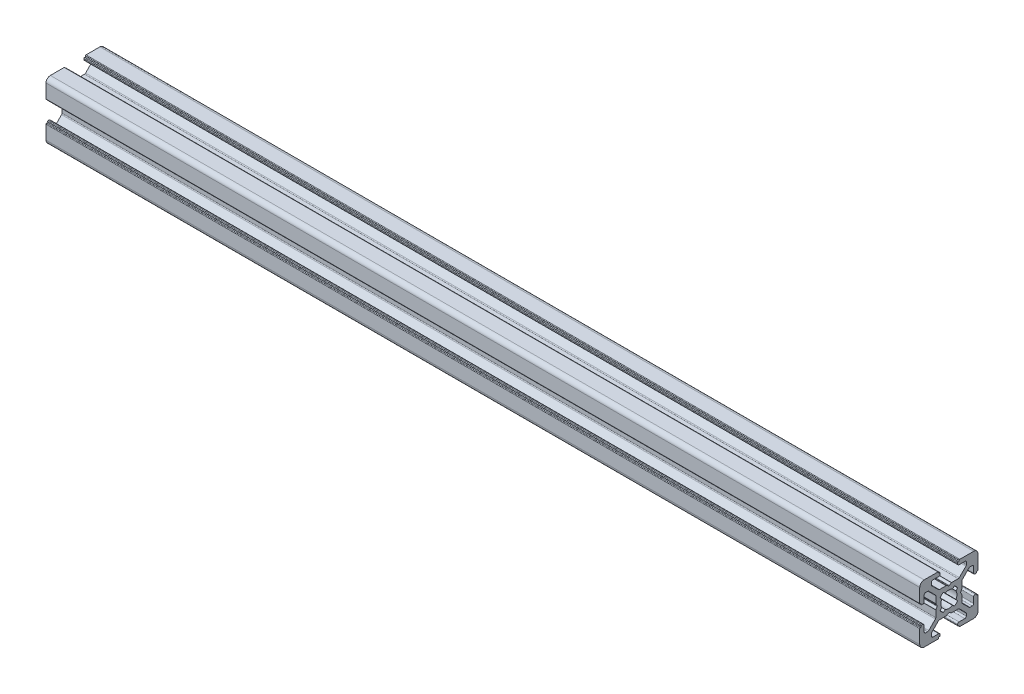
SolidWorks part; units mm, degrees
ref_plane "Front Plane" through (0, 0, 0) normal (0, 0, 1) x (1, 0, 0)
ref_plane "Top Plane" through (0, 0, 0) normal (0, 1, 0) x (1, 0, 0)
ref_plane "Right Plane" through (0, 0, 0) normal (1, 0, 0) x (0, 0, -1)
sketch "Sketch1" plane through (0, 0, 0) normal (0, 0, 1) x (1, 0, 0)
  line L0 (0, 0) -> (300, 0)
  dimension "D1" = 300
other "Metric 2020(1)"
ref_plane "Plane1" through (0, 0, 0) normal (1, 0, 0) x (0, 1, 0)
sketch "Sketch11" plane through (0, 0, 0) normal (1, 0, 0) x (0, 1, 0)
  line L0 (0, 10) -> (0, -10) construction
  line L1 (-10, 0) -> (10, 0) construction
  line L2 (-3.5, 8.5) -> (-5.5, 8.5)
  line L3 (-3.55, 9.7) -> (-3.55, 9.8)
  line L4 (-6, 7.2678) -> (-6, 8)
  line L5 (-7.2678, 6) -> (-8, 6)
  line L6 (-3.75, 10) -> (-8.5, 10)
  line L7 (-9.7, 3.55) -> (-9.8, 3.55)
  line L8 (-9.5, 3.2) -> (-9.5, 3.35)
  line L9 (-9, 3) -> (-9.3, 3)
  line L10 (-4.4732, 0.8536) -> (-4.0381, 0.1)
  line L11 (-4.5, 3.2322) -> (-4.5, 0.9536)
  line L12 (-8.5, 3.5) -> (-8.5, 5.5)
  line L13 (-10, 3.75) -> (-10, 8.5)
  line L14 (-3.5858, 4.6464) -> (-5.8536, 6.9142)
  line L15 (-4.6464, 3.5858) -> (-6.9142, 5.8536)
  line L16 (-3.2, 9.5) -> (-3.35, 9.5)
  line L17 (-3, 9) -> (-3, 9.3)
  line L18 (-0.8536, 4.4732) -> (-0.1, 4.0381)
  line L19 (-3.2322, 4.5) -> (-0.9536, 4.5)
  line L20 (-1.2582, 2.4453) -> (-1.9139, 2.9896)
  line L21 (-2.4453, 1.2582) -> (-2.9922, 1.9099)
  line L22 (3.5, -8.5) -> (5.5, -8.5)
  line L23 (3.55, -9.7) -> (3.55, -9.8)
  line L24 (6, -7.2678) -> (6, -8)
  line L25 (7.2678, -6) -> (8, -6)
  line L26 (3.75, -10) -> (8.5, -10)
  line L27 (9.7, -3.55) -> (9.8, -3.55)
  line L28 (9.5, -3.2) -> (9.5, -3.35)
  line L29 (9, -3) -> (9.3, -3)
  line L30 (4.4732, -0.8536) -> (4.0381, -0.1)
  line L31 (4.5, -3.2322) -> (4.5, -0.9536)
  line L32 (8.5, -3.5) -> (8.5, -5.5)
  line L33 (10, -3.75) -> (10, -8.5)
  line L34 (3.5858, -4.6464) -> (5.8536, -6.9142)
  line L35 (4.6464, -3.5858) -> (6.9142, -5.8536)
  line L36 (3.2, -9.5) -> (3.35, -9.5)
  line L37 (3, -9) -> (3, -9.3)
  line L38 (0.8536, -4.4732) -> (0.1, -4.0381)
  line L39 (3.2322, -4.5) -> (0.9536, -4.5)
  line L40 (1.2582, -2.4453) -> (1.9139, -2.9896)
  line L41 (2.4453, -1.2582) -> (2.9922, -1.9099)
  line L42 (-2.4453, -1.2582) -> (-2.9922, -1.9099)
  line L43 (-1.2582, -2.4453) -> (-1.9139, -2.9896)
  line L44 (-3.2322, -4.5) -> (-0.9536, -4.5)
  line L45 (-0.8536, -4.4732) -> (-0.1, -4.0381)
  line L46 (-3, -9) -> (-3, -9.3)
  line L47 (-3.2, -9.5) -> (-3.35, -9.5)
  line L48 (-4.6464, -3.5858) -> (-6.9142, -5.8536)
  line L49 (-3.5858, -4.6464) -> (-5.8536, -6.9142)
  line L50 (-10, -3.75) -> (-10, -8.5)
  line L51 (-8.5, -3.5) -> (-8.5, -5.5)
  line L52 (-4.5, -3.2322) -> (-4.5, -0.9536)
  line L53 (-4.4732, -0.8536) -> (-4.0381, -0.1)
  line L54 (-9, -3) -> (-9.3, -3)
  line L55 (-9.5, -3.2) -> (-9.5, -3.35)
  line L56 (-9.7, -3.55) -> (-9.8, -3.55)
  line L57 (2.4453, 1.2582) -> (2.9922, 1.9099)
  line L58 (1.2582, 2.4453) -> (1.9139, 2.9896)
  line L59 (3.2322, 4.5) -> (0.9536, 4.5)
  line L60 (0.8536, 4.4732) -> (0.1, 4.0381)
  line L61 (-3.75, -10) -> (-8.5, -10)
  line L62 (-7.2678, -6) -> (-8, -6)
  line L63 (-6, -7.2678) -> (-6, -8)
  line L64 (3, 9) -> (3, 9.3)
  line L65 (3.2, 9.5) -> (3.35, 9.5)
  line L66 (4.6464, 3.5858) -> (6.9142, 5.8536)
  line L67 (3.5858, 4.6464) -> (5.8536, 6.9142)
  line L68 (10, 3.75) -> (10, 8.5)
  line L69 (8.5, 3.5) -> (8.5, 5.5)
  line L70 (4.5, 3.2322) -> (4.5, 0.9536)
  line L71 (4.4732, 0.8536) -> (4.0381, 0.1)
  line L72 (9, 3) -> (9.3, 3)
  line L73 (9.5, 3.2) -> (9.5, 3.35)
  line L74 (9.7, 3.55) -> (9.8, 3.55)
  line L75 (3.75, 10) -> (8.5, 10)
  line L76 (7.2678, 6) -> (8, 6)
  line L77 (6, 7.2678) -> (6, 8)
  line L78 (3.55, 9.7) -> (3.55, 9.8)
  line L79 (3.5, 8.5) -> (5.5, 8.5)
  line L80 (-3.55, -9.7) -> (-3.55, -9.8)
  line L81 (-3.5, -8.5) -> (-5.5, -8.5)
  line L83 (10, -10) -> (-10, -10) construction
  line L84 (10, -10) -> (10, 10) construction
  line L85 (10, 10) -> (-10, 10) construction
  line L86 (-10, -10) -> (-10, 10) construction
  line L87 (10, -10) -> (-10, 10) construction
  line L88 (10, 10) -> (-10, -10) construction
  arc A0 (-10, 8.5) -> (-8.5, 10) centre (-8.5, 8.5) cw
  arc A1 (-8.5, 5.5) -> (-8, 6) centre (-8, 5.5) cw
  arc A2 (-7.2678, 6) -> (-6.9142, 5.8536) centre (-7.2678, 5.5) cw
  arc A3 (-5.8536, 6.9142) -> (-6, 7.2678) centre (-5.5, 7.2678) cw
  arc A4 (-6, 8) -> (-5.5, 8.5) centre (-5.5, 8) cw
  arc A5 (-9.7, 3.55) -> (-9.5, 3.35) centre (-9.7, 3.35) cw
  arc A6 (-9.8, 3.55) -> (-10, 3.75) centre (-9.8, 3.75) cw
  arc A7 (-9.3, 3) -> (-9.5, 3.2) centre (-9.3, 3.2) cw
  arc A8 (-8.5, 3.5) -> (-9, 3) centre (-9, 3.5) cw
  arc A9 (-4.6464, 3.5858) -> (-4.5, 3.2322) centre (-5, 3.2322) cw
  arc A10 (-4.4732, 0.8536) -> (-4.5, 0.9536) centre (-4.3, 0.9536) cw
  arc A11 (-4.0381, 0.1) -> (-4.0381, -0.1) centre (-4.2113, 0) cw
  arc A12 (-3.2, 9.5) -> (-3, 9.3) centre (-3.2, 9.3) cw
  arc A13 (-0.9536, 4.5) -> (-0.8536, 4.4732) centre (-0.9536, 4.3) cw
  arc A14 (-2.9922, 1.9099) -> (-1.9139, 2.9896) centre (0, 0) cw
  arc A15 (-3.2322, 4.5) -> (-3.5858, 4.6464) centre (-3.2322, 5) cw
  arc A16 (-3.75, 10) -> (-3.55, 9.8) centre (-3.75, 9.8) cw
  arc A17 (-3.35, 9.5) -> (-3.55, 9.7) centre (-3.35, 9.7) cw
  arc A18 (2.4453, -1.2582) -> (2.4453, 1.2582) centre (0, 0) ccw
  arc A19 (-3, 9) -> (-3.5, 8.5) centre (-3.5, 9) cw
  arc A20 (-2.4453, -1.2582) -> (-2.4453, 1.2582) centre (0, 0) cw
  arc A21 (10, -8.5) -> (8.5, -10) centre (8.5, -8.5) cw
  arc A22 (8.5, -5.5) -> (8, -6) centre (8, -5.5) cw
  arc A23 (7.2678, -6) -> (6.9142, -5.8536) centre (7.2678, -5.5) cw
  arc A24 (5.8536, -6.9142) -> (6, -7.2678) centre (5.5, -7.2678) cw
  arc A25 (6, -8) -> (5.5, -8.5) centre (5.5, -8) cw
  arc A26 (9.7, -3.55) -> (9.5, -3.35) centre (9.7, -3.35) cw
  arc A27 (9.8, -3.55) -> (10, -3.75) centre (9.8, -3.75) cw
  arc A28 (9.3, -3) -> (9.5, -3.2) centre (9.3, -3.2) cw
  arc A29 (8.5, -3.5) -> (9, -3) centre (9, -3.5) cw
  arc A30 (4.6464, -3.5858) -> (4.5, -3.2322) centre (5, -3.2322) cw
  arc A31 (4.4732, -0.8536) -> (4.5, -0.9536) centre (4.3, -0.9536) cw
  arc A32 (3.2, -9.5) -> (3, -9.3) centre (3.2, -9.3) cw
  arc A33 (-0.1, -4.0381) -> (0.1, -4.0381) centre (0, -4.2113) cw
  arc A34 (0.9536, -4.5) -> (0.8536, -4.4732) centre (0.9536, -4.3) cw
  arc A35 (2.9922, -1.9099) -> (1.9139, -2.9896) centre (0, 0) cw
  arc A36 (1.2582, -2.4453) -> (-1.2582, -2.4453) centre (0, 0) cw
  arc A37 (3.2322, -4.5) -> (3.5858, -4.6464) centre (3.2322, -5) cw
  arc A38 (3.75, -10) -> (3.55, -9.8) centre (3.75, -9.8) cw
  arc A39 (3.35, -9.5) -> (3.55, -9.7) centre (3.35, -9.7) cw
  arc A40 (3, -9) -> (3.5, -8.5) centre (3.5, -9) cw
  arc A41 (-3, -9) -> (-3.5, -8.5) centre (-3.5, -9) ccw
  arc A42 (-3.35, -9.5) -> (-3.55, -9.7) centre (-3.35, -9.7) ccw
  arc A43 (-3.75, -10) -> (-3.55, -9.8) centre (-3.75, -9.8) ccw
  arc A44 (-3.2322, -4.5) -> (-3.5858, -4.6464) centre (-3.2322, -5) ccw
  arc A45 (-2.9922, -1.9099) -> (-1.9139, -2.9896) centre (0, 0) ccw
  arc A46 (-0.9536, -4.5) -> (-0.8536, -4.4732) centre (-0.9536, -4.3) ccw
  arc A47 (-3.2, -9.5) -> (-3, -9.3) centre (-3.2, -9.3) ccw
  arc A48 (-4.4732, -0.8536) -> (-4.5, -0.9536) centre (-4.3, -0.9536) ccw
  arc A49 (3, 9) -> (3.5, 8.5) centre (3.5, 9) ccw
  arc A50 (3.35, 9.5) -> (3.55, 9.7) centre (3.35, 9.7) ccw
  arc A51 (3.75, 10) -> (3.55, 9.8) centre (3.75, 9.8) ccw
  arc A52 (3.2322, 4.5) -> (3.5858, 4.6464) centre (3.2322, 5) ccw
  arc A53 (1.2582, 2.4453) -> (-1.2582, 2.4453) centre (0, 0) ccw
  arc A54 (-4.6464, -3.5858) -> (-4.5, -3.2322) centre (-5, -3.2322) ccw
  arc A55 (-8.5, -3.5) -> (-9, -3) centre (-9, -3.5) ccw
  arc A56 (-9.3, -3) -> (-9.5, -3.2) centre (-9.3, -3.2) ccw
  arc A57 (-9.8, -3.55) -> (-10, -3.75) centre (-9.8, -3.75) ccw
  arc A58 (-9.7, -3.55) -> (-9.5, -3.35) centre (-9.7, -3.35) ccw
  arc A59 (-6, -8) -> (-5.5, -8.5) centre (-5.5, -8) ccw
  arc A60 (2.9922, 1.9099) -> (1.9139, 2.9896) centre (0, 0) ccw
  arc A61 (0.9536, 4.5) -> (0.8536, 4.4732) centre (0.9536, 4.3) ccw
  arc A62 (-0.1, 4.0381) -> (0.1, 4.0381) centre (0, 4.2113) ccw
  arc A63 (-5.8536, -6.9142) -> (-6, -7.2678) centre (-5.5, -7.2678) ccw
  arc A64 (-7.2678, -6) -> (-6.9142, -5.8536) centre (-7.2678, -5.5) ccw
  arc A65 (-8.5, -5.5) -> (-8, -6) centre (-8, -5.5) ccw
  arc A66 (-10, -8.5) -> (-8.5, -10) centre (-8.5, -8.5) ccw
  arc A67 (3.2, 9.5) -> (3, 9.3) centre (3.2, 9.3) ccw
  arc A68 (4.0381, 0.1) -> (4.0381, -0.1) centre (4.2113, 0) ccw
  arc A69 (4.4732, 0.8536) -> (4.5, 0.9536) centre (4.3, 0.9536) ccw
  arc A70 (4.6464, 3.5858) -> (4.5, 3.2322) centre (5, 3.2322) ccw
  arc A71 (8.5, 3.5) -> (9, 3) centre (9, 3.5) ccw
  arc A72 (9.3, 3) -> (9.5, 3.2) centre (9.3, 3.2) ccw
  arc A73 (9.8, 3.55) -> (10, 3.75) centre (9.8, 3.75) ccw
  arc A74 (9.7, 3.55) -> (9.5, 3.35) centre (9.7, 3.35) ccw
  arc A75 (6, 8) -> (5.5, 8.5) centre (5.5, 8) ccw
  arc A76 (5.8536, 6.9142) -> (6, 7.2678) centre (5.5, 7.2678) ccw
  arc A77 (7.2678, 6) -> (6.9142, 5.8536) centre (7.2678, 5.5) ccw
  arc A78 (8.5, 5.5) -> (8, 6) centre (8, 5.5) ccw
  arc A79 (10, 8.5) -> (8.5, 10) centre (8.5, 8.5) ccw
  point P241 (0, 0)
  dimension "D4" = 5.5
  dimension "D1" = 6
  dimension "D2" = 20
  dimension "D3" = 20
  dimension "D5" = 5.5
  dimension "D6" = 10
  dimension "D7" = 6
  dimension "D8" = 6
  dimension "D9" = 6
